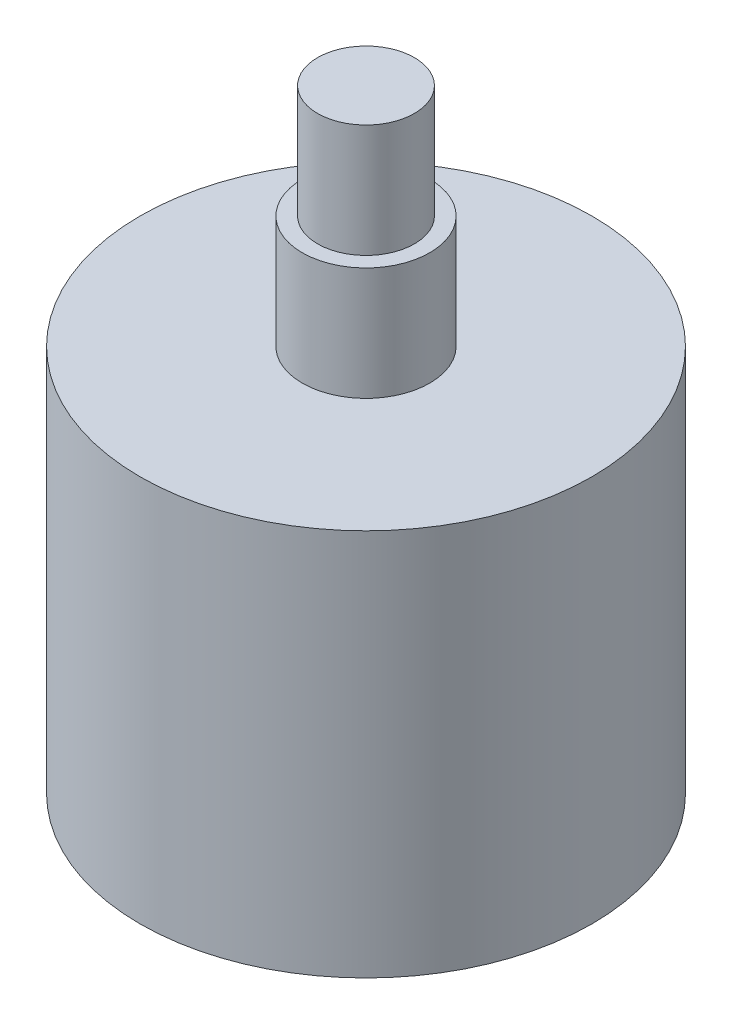
SolidWorks part; units mm, degrees
ref_plane "前视基准面" through (0, 0, 0) normal (0, 0, 1) x (1, 0, 0)
ref_plane "上视基准面" through (0, 0, 0) normal (0, 1, 0) x (1, 0, 0)
ref_plane "右视基准面" through (0, 0, 0) normal (1, 0, 0) x (0, 0, -1)
sketch "Sketch2" plane through (0, 0, 0) normal (0, 1, 0) x (1, 0, 0)
  circle A0 centre (0, 0) radius 14
  dimension "D1" = 28
extrude "Boss-Extrude1" add sketch "Sketch2" along normal blind 24
sketch "Sketch3" plane through (0, 24, 0) normal (0, 1, 0) x (1, 0, 0)
  circle A0 centre (0, 0) radius 3.95
  dimension "D1" = 7.9
extrude "Boss-Extrude2" add sketch "Sketch3" along normal blind 7
sketch "Sketch4" plane through (0, 31, 0) normal (0, 1, 0) x (1, 0, 0)
  circle A0 centre (0, 0) radius 3
  dimension "D1" = 6
extrude "Boss-Extrude3" add sketch "Sketch4" along normal blind 7
sketch "Sketch6" plane through (0, 0, 0) normal (0, -1, 0) x (1, 0, 0)
  line L0 (0, 0) -> (9.5, 0) construction
  circle A0 centre (9.5, 0) radius 1.5
  circle A1 centre (0, -9.5) radius 1.5
  circle A2 centre (-9.5, 0) radius 1.5
  circle A3 centre (0, 9.5) radius 1.5
  point P13 (0, 0)
  dimension "D1" = 9.5
  dimension "D2" = 3
  dimension "D3" = 4
extrude "Cut-Extrude1" cut sketch "Sketch6" against normal blind 5
